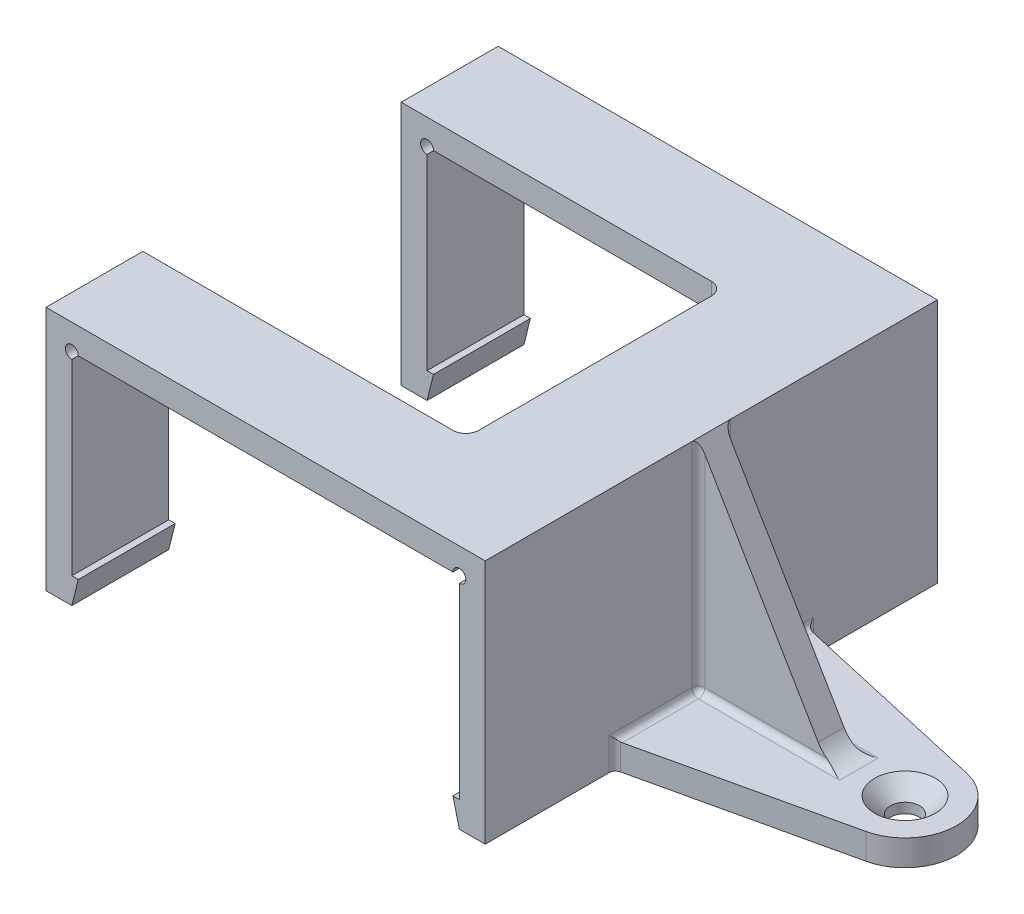
SolidWorks part; units mm, degrees
ref_plane "Plan de face" through (0, 0, 0) normal (0, 0, 1) x (1, 0, 0)
ref_plane "Plan de dessus" through (0, 0, 0) normal (0, 1, 0) x (1, 0, 0)
ref_plane "Plan de droite" through (0, 0, 0) normal (1, 0, 0) x (0, 0, -1)
sketch "Esquisse1" plane through (0, 0, 0) normal (0, 0, 1) x (1, 0, 0)
  line L0 (0, -38) -> (0, 0)
  line L1 (0, 0) -> (68, 0)
  line L2 (68, 0) -> (68, -38)
  line L3 (68, -38) -> (64, -38)
  line L4 (64, -38) -> (63, -34)
  line L5 (63, -34) -> (64, -34)
  line L6 (64, -34) -> (64, -4)
  line L7 (64, -4) -> (4, -4)
  line L8 (4, -4) -> (4, -34)
  line L9 (4, -34) -> (5, -34)
  line L10 (5, -34) -> (4, -38)
  line L11 (4, -38) -> (0, -38)
  dimension "D2" = 4
  dimension "D3" = 4
  dimension "D4" = 4
  dimension "D5" = 4
  dimension "D6" = 4
  dimension "D7" = 1
  dimension "D8" = 4
  dimension "D9" = 1
  dimension "D10" = 4
extrude "Forme principale" add sketch "Esquisse1" along normal mid plane 70
sketch "Esquisse3" plane through (0, 0, 0) normal (0, 1, 0) x (1, 0, 0)
  line L0 (50, 20) -> (0, 20)
  line L1 (50, 20) -> (50, -20)
  line L2 (0, 20) -> (0, -20)
  line L3 (50, -20) -> (0, -20)
  line L4 (50, 20) -> (0, -20) construction
  line L5 (0, 20) -> (50, -20) construction
  line L6 (0, -35) -> (0, 35) construction
  point P1 (25, 0)
  dimension "D1" = 40
  dimension "D2" = 50
extrude "Évidement" cut sketch "Esquisse3" against normal through all
sketch "Esquisse4" plane through (0, -38, 0) normal (0, -1, 0) x (1, 0, 0)
  line L0 (68, 15) -> (99.7678, 7.8022)
  line L1 (68, 35) -> (68, -35) construction
  line L2 (99.7678, -7.8022) -> (68, -15)
  line L3 (68, -15) -> (68, 15)
  arc A0 (99.7678, 7.8022) -> (99.7678, -7.8022) centre (98, 0) cw
  point P6 (68, 0)
  dimension "D2" = 8
  dimension "D1" = 30
  dimension "D3" = 30
extrude "Bossage écrou" add sketch "Esquisse4" against normal blind 4
hole_wizard "Fraisage pour vis à tête fraisée M41" positions "Esquisse8" profile "Esquisse7" countersink size "M4" standard "ISO" end condition through all
sketch "Esquisse8" plane through (0, -34, 0) normal (0, 1, 0) x (1, 0, 0)
  point P0 (98, 0)
  point P3 (98, 0)
sketch "Esquisse7" plane through (98, -34, 0) normal (1, 0, 0) x (0, 0, 1)
  line L0 (0, 0) -> (0, 4.0001)
  line L1 (0, 4.0001) -> (2.25, 4.0001)
  line L2 (2.25, 4.0001) -> (2.25, 2.45)
  line L3 (2.25, 2.45) -> (4.7, 0)
  line L5 (4.7, 0) -> (0, 0)
  line L6 (-2.25, 2.45) -> (-4.7, 0) construction
  line L11 (0, -6.35) -> (0, 107.95) construction
  dimension "Diamètre du perçage jusqu'au prochain" = 4.5
  dimension "Profondeur du perçage jusqu'au prochain" = 4.0001
  dimension "Diamètre du fraisage entrant" = 9.4
  dimension "Angle du fraisage entrant" = 90
sketch "Esquisse9" plane through (0, 0, 0) normal (0, 0, 1) x (1, 0, 0)
  line L0 (68, 0) -> (88, -34)
  line L3 (98, -34) -> (98, -38) construction
  dimension "D1" = 10
rib "Nervure3" sketch "Esquisse9" sketch "Esquisse9" thickness 4 extrusion direction parallel to sketch draft on no parameters "D1"=4
fillet "Congé2" radius 1 8 edges at (68, -34, -8.5) (78, -34, -2) (68, -17, -2) (78, -34, 2) (68, -34, 8.5) (68, -17, 2)
fillet "Congé3" radius 5 1 edges at (88, -34, 0)
fillet "Congé4" radius 2 2 edges at (50, -2, -20) (50, -2, 20)
sketch "Esquisse10" plane through (0, 0, -35) normal (0, 0, -1) x (-1, 0, 0)
  circle A0 centre (-64, -4) radius 1
  circle A1 centre (-4, -4) radius 1
  dimension "D1" = 2
  dimension "D2" = 2
extrude "Enlèv. mat.-Extru.1" cut sketch "Esquisse10" against normal through all
sketch "Esquisse11" plane through (0, -34, 0) normal (0, 1, 0) x (1, 0, 0)
  line L0 (63, -35) -> (63, 35) construction
  line L1 (64, 20) -> (63, 20)
  line L2 (64, 20) -> (64, -20)
  line L3 (64, -20) -> (63, -20)
  line L4 (63, 20) -> (63, -20)
  line L5 (64, -35) -> (64, 35) construction
extrude "Enlèv. mat.-Extru.2" cut sketch "Esquisse11" against normal through all
